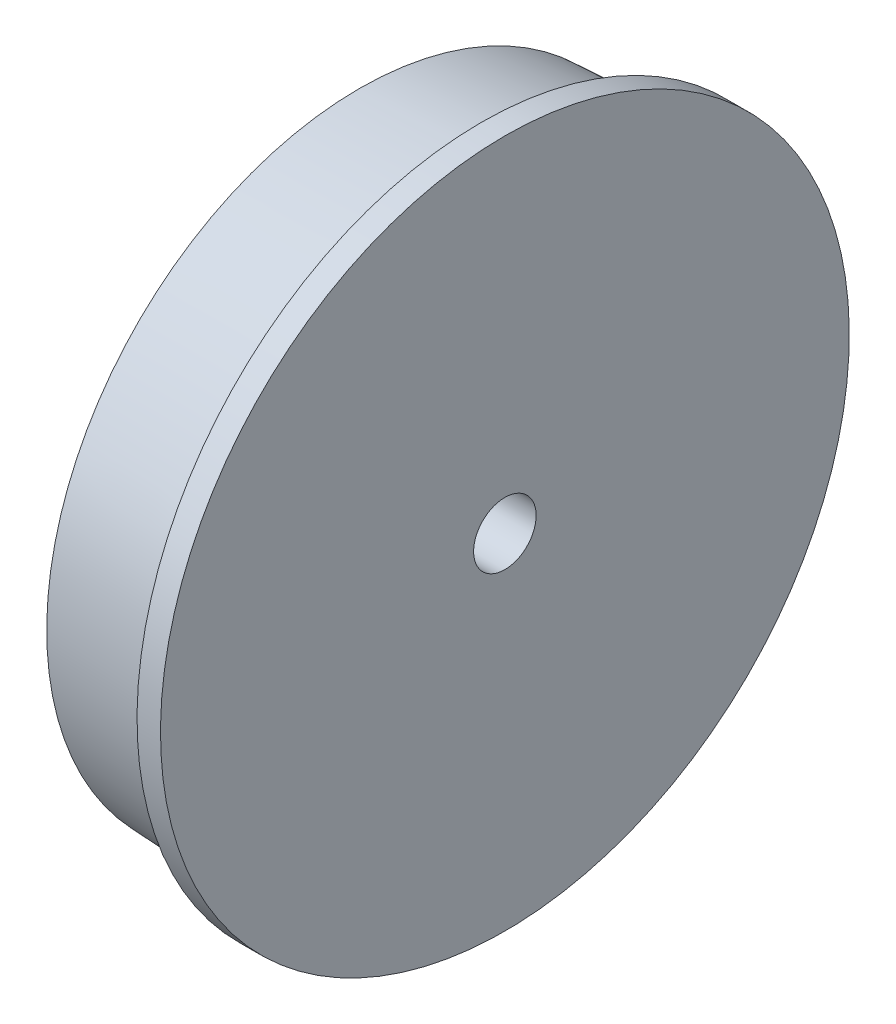
SolidWorks part; units mm, degrees
material "AISI 1020 Steel, Cold Rolled"
ref_plane "Front Plane" through (0, 0, 0) normal (0, 0, 1) x (1, 0, 0)
ref_plane "Top Plane" through (0, 0, 0) normal (0, 1, 0) x (1, 0, 0)
ref_plane "Right Plane" through (0, 0, 0) normal (1, 0, 0) x (0, 0, -1)
sketch "Sketch1" plane through (0, 0, 0) normal (0, 0, 1) x (1, 0, 0)
  line L0 (0, 0) -> (-78, 0)
  line L1 (-78, 0) -> (-78, 200)
  line L2 (-78, 200) -> (0, 200) construction
  line L3 (0, 0) -> (0, 204.0878)
  line L4 (0, 204.0878) -> (-78, 200)
  dimension "D1" = 3
  dimension "D2" = 78
  dimension "D3" = 200
revolve "Revolve1" add sketch "Sketch1" angle 360 about L0
sketch "Sketch2" plane through (-78, 0, 0) normal (-1, 0, 0) x (0, 0, 1)
  circle A0 centre (0, 0) radius 20
  dimension "D1" = 40
extrude "Cut-Extrude1" cut sketch "Sketch2" against normal through all
sketch "Sketch3" plane through (0, 0, 0) normal (1, 0, 0) x (0, 0, -1)
  circle A0 centre (0, 0) radius 220.2516
  circle A1 centre (0, 0) radius 20
  circle M1 centre (0, 0) radius 20
  circle M2 centre (0, 0) radius 204.0878
extrude "Boss-Extrude1" add sketch "Sketch3" along normal blind 15 contours M2 M1 | A0 M2 | A1
fillet "Fillet1" [suppressed] radius 5
fillet "Fillet2" [suppressed] radius 5
ref_plane "Plane1" [suppressed] through (0, 0, 0) normal (-1, 0, 0) x (0, 0, 1)
